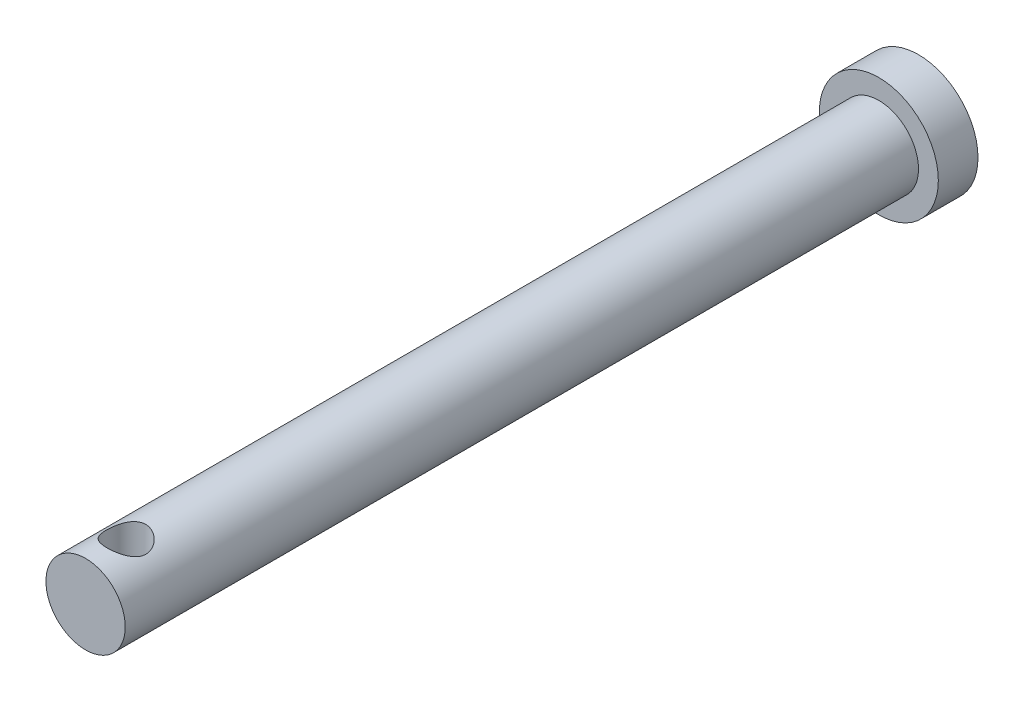
SolidWorks part; units mm, degrees
ref_plane "Front Plane" through (0, 0, 0) normal (0, 0, 1) x (1, 0, 0)
ref_plane "Top Plane" through (0, 0, 0) normal (0, 1, 0) x (1, 0, 0)
ref_plane "Right Plane" through (0, 0, 0) normal (1, 0, 0) x (0, 0, -1)
sketch "Sketch2" plane through (0, 0, 0) normal (0, 1, 0) x (1, 0, 0)
  line L1 (-3.175, -66.675) -> (3.175, -66.675)
  line L2 (-3.175, -66.675) -> (-3.175, 66.675)
  line L3 (-3.175, 66.675) -> (3.175, 66.675)
  line L4 (3.175, -66.675) -> (3.175, 66.675)
  line L5 (-3.175, -66.675) -> (3.175, 66.675) construction
  line L6 (-3.175, 66.675) -> (3.175, -66.675) construction
  line L7 (-3.175, 66.675) -> (-6.35, 66.675)
  line L8 (-3.175, 66.675) -> (-3.175, 60.325)
  line L9 (-3.175, 60.325) -> (-6.35, 60.325)
  line L10 (-6.35, 66.675) -> (-6.35, 60.325)
  point P0 (0, 0)
  dimension "D1" = 133.35
  dimension "D2" = 6.35
  dimension "D3" = 3.175
  dimension "D4" = 6.35
revolve "Revolve1" add sketch "Sketch2" angle 360 about L4
sketch "Sketch5" plane through (0, 0, 0) normal (0, 1, 0) x (1, 0, 0)
  line L0 (-3.175, -66.675) -> (9.525, -66.675) construction
  circle A0 centre (3.3184, -60.325) radius 3.175
  dimension "D1" = 6.35
  dimension "D2" = 6.35
extrude "Cut-Extrude2" cut sketch "Sketch5" against normal through all both and the other way through all contours A0
